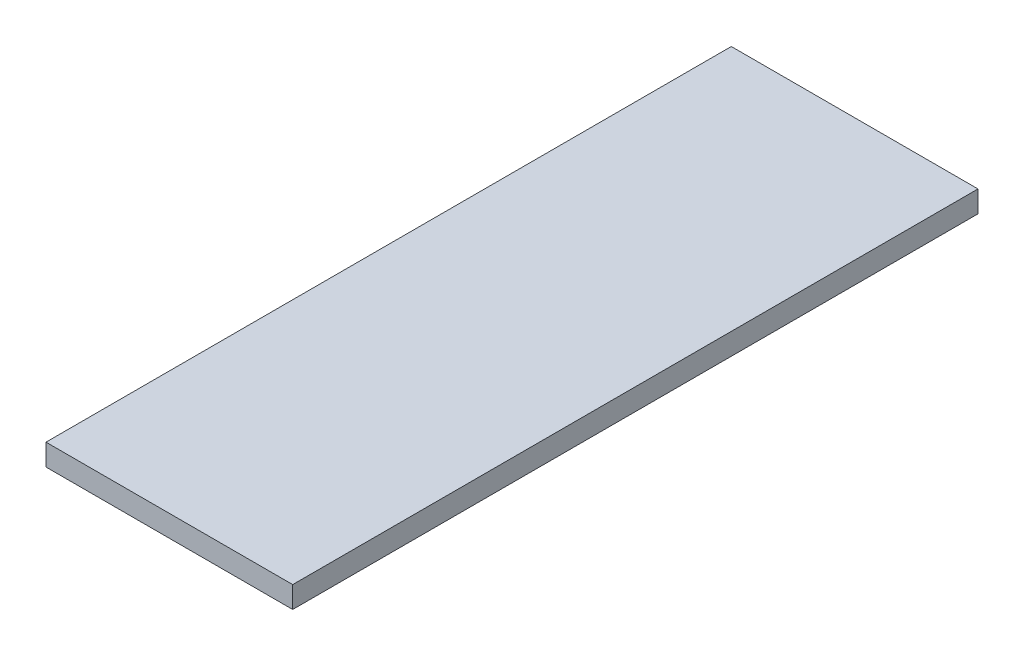
SolidWorks part; units mm, degrees
ref_plane "Front Plane" through (0, 0, 0) normal (0, 0, 1) x (1, 0, 0)
ref_plane "Top Plane" through (0, 0, 0) normal (0, 1, 0) x (1, 0, 0)
ref_plane "Right Plane" through (0, 0, 0) normal (1, 0, 0) x (0, 0, -1)
sketch "Sketch1" plane through (0, 0, 0) normal (0, 1, 0) x (1, 0, 0)
  line L1 (-28.575, 79.375) -> (28.575, 79.375)
  line L2 (-28.575, 79.375) -> (-28.575, -79.375)
  line L3 (-28.575, -79.375) -> (28.575, -79.375)
  line L4 (28.575, 79.375) -> (28.575, -79.375)
  point P4 (28.575, 0)
  point P6 (0, 79.375)
  dimension "D1" = 57.15
  dimension "D2" = 158.75
extrude "Boss-Extrude1" add sketch "Sketch1" along normal blind 5
